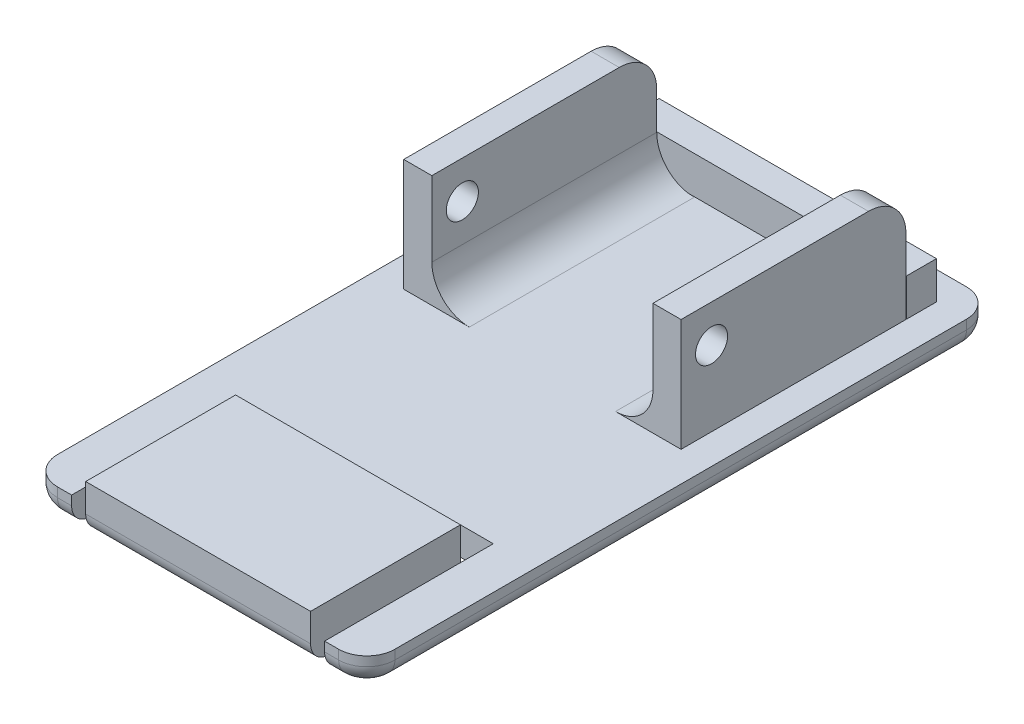
SolidWorks part; units mm, degrees
ref_plane "前视基准面" through (0, 0, 0) normal (0, 0, 1) x (1, 0, 0)
ref_plane "上视基准面" through (0, 0, 0) normal (0, 1, 0) x (1, 0, 0)
ref_plane "右视基准面" through (0, 0, 0) normal (1, 0, 0) x (0, 0, -1)
sketch "草图1" plane through (0, 0, 0) normal (0, 1, 0) x (1, 0, 0)
  line L1 (-9, 16.75) -> (9, 16.75)
  line L2 (-9, 16.75) -> (-9, -16.75)
  line L3 (-9, -16.75) -> (9, -16.75)
  line L4 (9, 16.75) -> (9, -16.75)
  dimension "D1" = 18
  dimension "D2" = 33.5
  dimension "D3" = 16.75
  dimension "D4" = 9
extrude "凸台-拉伸1" add sketch "草图1" along normal blind 1.5
fillet "圆角1" radius 1.5 4 edges at (9, 0.75, 16.75) (-9, 0.75, 16.75) (9, 0.75, -16.75) (-9, 0.75, -16.75)
sketch "草图2" plane through (0, 1.5, 0) normal (0, 1, 0) x (1, 0, 0)
  line L0 (-9, 15.25) -> (-9, -15.25) construction
  line L1 (-7.4, 13.6224) -> (-5.9, 13.6224)
  line L2 (-7.4, 13.6224) -> (-7.4, 1.6224)
  line L3 (-7.4, 1.6224) -> (-5.9, 1.6224)
  line L4 (-5.9, 13.6224) -> (-5.9, 1.6224)
  line L5 (0, 13.01) -> (0, -10.9624) construction
  line L6 (5.9, 13.6224) -> (5.9, 1.6224)
  line L7 (7.4, 1.6224) -> (5.9, 1.6224)
  line L8 (7.4, 13.6224) -> (7.4, 1.6224)
  line L9 (7.4, 13.6224) -> (5.9, 13.6224)
  dimension "D1" = 1.5
  dimension "D2" = 1.6
  dimension "D3" = 12
extrude "凸台-拉伸2" add sketch "草图2" along normal blind 6
sketch "草图3" plane through (0, 1.5, 0) normal (0, 1, 0) x (1, 0, 0)
  line L0 (7.4, 1.6224) -> (7.4, 13.6224) construction
  line L1 (-7.4, 15.25) -> (7.4, 15.25)
  line L2 (-7.4, 15.25) -> (-7.4, 13.65)
  line L3 (-7.4, 13.65) -> (7.4, 13.65)
  line L4 (7.4, 15.25) -> (7.4, 13.65)
  line L5 (7.4, 1.6224) -> (7.4, 13.6224) construction
  line L6 (7.5, 16.75) -> (-7.5, 16.75) construction
  line L7 (-9, 15.25) -> (-9, -15.25) construction
  dimension "D1" = 1.5
  dimension "D2" = 1.6
  dimension "D3" = 1.6
extrude "凸台-拉伸3" add sketch "草图3" along normal blind 2
fillet "圆角2" radius 2 4 edges at (-6.65, 7.5, -13.6224) (6.65, 7.5, -13.6224) (-5.9, 1.5, -7.6224) (5.9, 1.5, -7.6224)
sketch "草图4" plane through (7.4, 0, 0) normal (1, 0, 0) x (0, 0, -1)
  line L0 (15.25, 0) -> (15.25, 1.5) construction
  line L1 (-15.25, 1.5) -> (15.25, 1.5) construction
  circle A0 centre (3.25, 5.5) radius 0.8565
  dimension "D1" = 12
  dimension "D2" = 4
extrude "切除-拉伸1" cut sketch "草图4" against normal blind 18
sketch "草图5" plane through (0, 1.5, 0) normal (0, 1, 0) x (1, 0, 0)
  line L7 (-7.5, -16.75) -> (7.5, -16.75) construction
  line L12 (-6, -16.75) -> (6, -16.75)
  line L13 (-6, -16.75) -> (-6, -8.75)
  line L14 (-6, -8.75) -> (6, -8.75)
  line L15 (6, -16.75) -> (6, -8.75)
  line L16 (-9, 15.25) -> (-9, -15.25) construction
  dimension "D1" = 8
  dimension "D2" = 12
  dimension "D3" = 3
extrude "凸台-拉伸4" add sketch "草图5" along normal blind 1
fillet "圆角3" radius 1 8 edges at (8.5607, 0, -16.3107) (0, 0, -16.75) (-8.5607, 0, -16.3107) (-9, 0, 0) (-8.5607, 0, 16.3107) (0, 0, 16.75) (8.5607, 0, 16.3107) (9, 0, 0)
sketch "草图6" plane through (0, 1.5, 0) normal (0, 1, 0) x (1, 0, 0)
  line L17 (-6, -16.75) -> (-6.75, -16.75)
  line L18 (-6.75, -16.75) -> (-6.75, -7.75)
  line L19 (-6.75, -7.75) -> (-3, -7.75)
  line L20 (-3, -7.75) -> (-3, -8.75)
  line L21 (6, -8.75) -> (-6, -8.75) construction
  line L22 (-3, -8.75) -> (-6, -8.75)
  line L23 (-6, -8.75) -> (-6, -16.75) construction
  line L24 (-6, -8.75) -> (-6, -16.75)
  line L26 (6, -8.75) -> (6, -16.75)
  line L27 (3, -8.75) -> (6, -8.75)
  line L28 (3, -7.75) -> (3, -8.75)
  line L29 (6.75, -7.75) -> (3, -7.75)
  line L30 (6.75, -16.75) -> (6.75, -7.75)
  line L31 (6, -16.75) -> (6.75, -16.75)
  dimension "D1" = 0.75
  dimension "D2" = 3
  dimension "D3" = 1
extrude "切除-拉伸2" cut sketch "草图6" against normal blind 10
